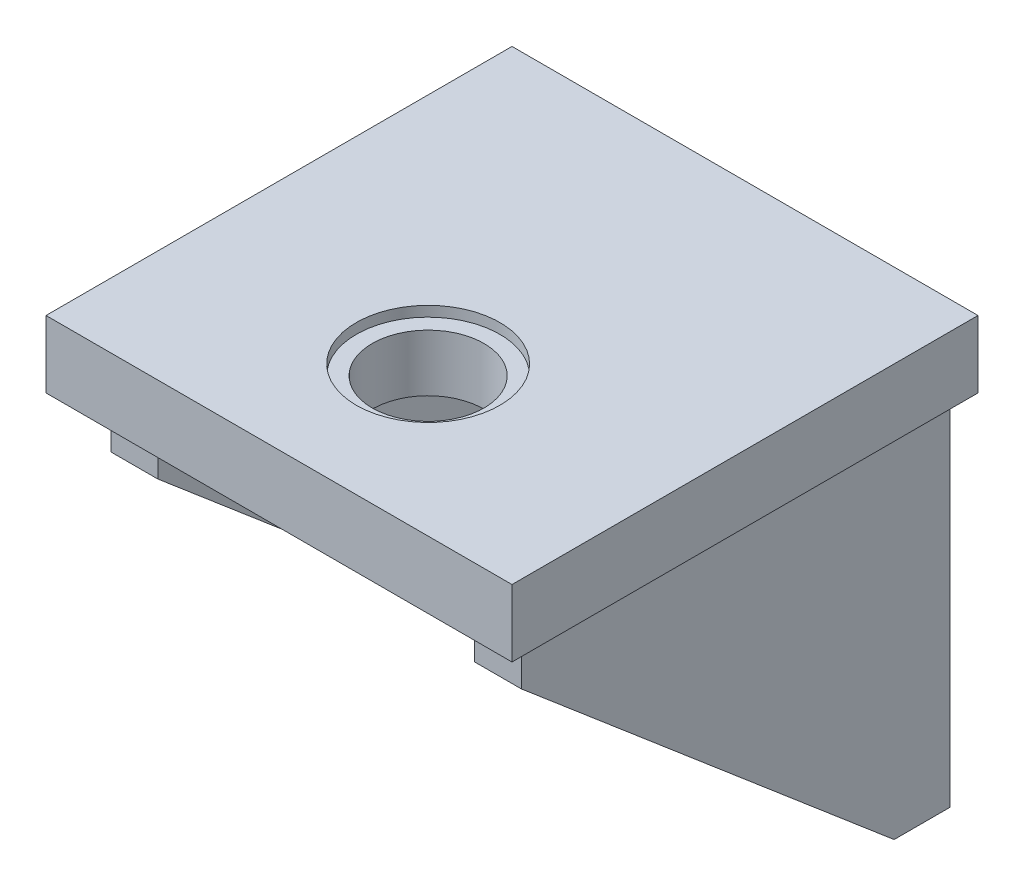
SolidWorks part; units mm, degrees
ref_plane "前视基准面" through (0, 0, 0) normal (0, 0, 1) x (1, 0, 0)
ref_plane "上视基准面" through (0, 0, 0) normal (0, 1, 0) x (1, 0, 0)
ref_plane "右视基准面" through (0, 0, 0) normal (1, 0, 0) x (0, 0, -1)
sketch "草图1" plane through (0, 0, 0) normal (0, 1, 0) x (1, 0, 0)
  line L1 (0, 0) -> (250, 0)
  line L2 (0, 0) -> (0, -250)
  line L3 (0, -250) -> (250, -250)
  line L4 (250, 0) -> (250, -250)
  dimension "D1" = 250
  dimension "D2" = 250
extrude "凸台-拉伸1" add sketch "草图1" along normal blind 36
sketch "草图2" plane through (0, 36, 0) normal (0, 1, 0) x (1, 0, 0)
  line L0 (125, 0) -> (125, -250) construction
  line L1 (250, 0) -> (0, 0) construction
  line L2 (0, -250) -> (250, -250) construction
  circle A0 centre (125, -170) radius 30
  point P8 (0, 0)
  dimension "D2" = 60
  dimension "D1" = 170
extrude "切除-拉伸1" cut sketch "草图2" against normal up to next
sketch "草图3" plane through (0, 36, 0) normal (0, 1, 0) x (1, 0, 0)
  circle A0 centre (125, -170) radius 38.5
  dimension "D1" = 77
extrude "切除-拉伸2" cut sketch "草图3" against normal blind 5.5
sketch "草图4" plane through (0, 0, 0) normal (0, -1, 0) x (1, 0, 0)
  line L0 (250, 0) -> (0, 0) construction
  line L1 (15, 0) -> (40, 0)
  line L2 (15, 0) -> (15, 230)
  line L3 (15, 230) -> (40, 230)
  line L4 (40, 0) -> (40, 230)
  line L5 (125, 250) -> (125, 0) construction
  line L6 (0, 250) -> (250, 250) construction
  dimension "D1" = 230
  dimension "D2" = 25
  dimension "D3" = 85
extrude "凸台-拉伸2" add sketch "草图4" along normal blind 200
sketch "草图5" plane through (15, 0, 0) normal (-1, 0, 0) x (0, 0, 1)
  line L0 (30, -200) -> (230, -30)
  line L1 (230, -200) -> (0, -200) construction
  line L2 (230, -200) -> (230, 0) construction
  line L3 (0, 0) -> (250, 0) construction
  line L4 (230, -30) -> (230, -200)
  line L5 (230, -200) -> (30, -200)
  dimension "D1" = 30
  dimension "D2" = 30
extrude "切除-拉伸3" cut sketch "草图5" against normal up to next
ref_plane "基准面1" through (125, 0, 0) normal (1, 0, 0) x (0, 0, -1)
mirror "镜向1" about plane through (125, 0, 0) normal (1, 0, 0) of "凸台-拉伸2", "切除-拉伸3"
